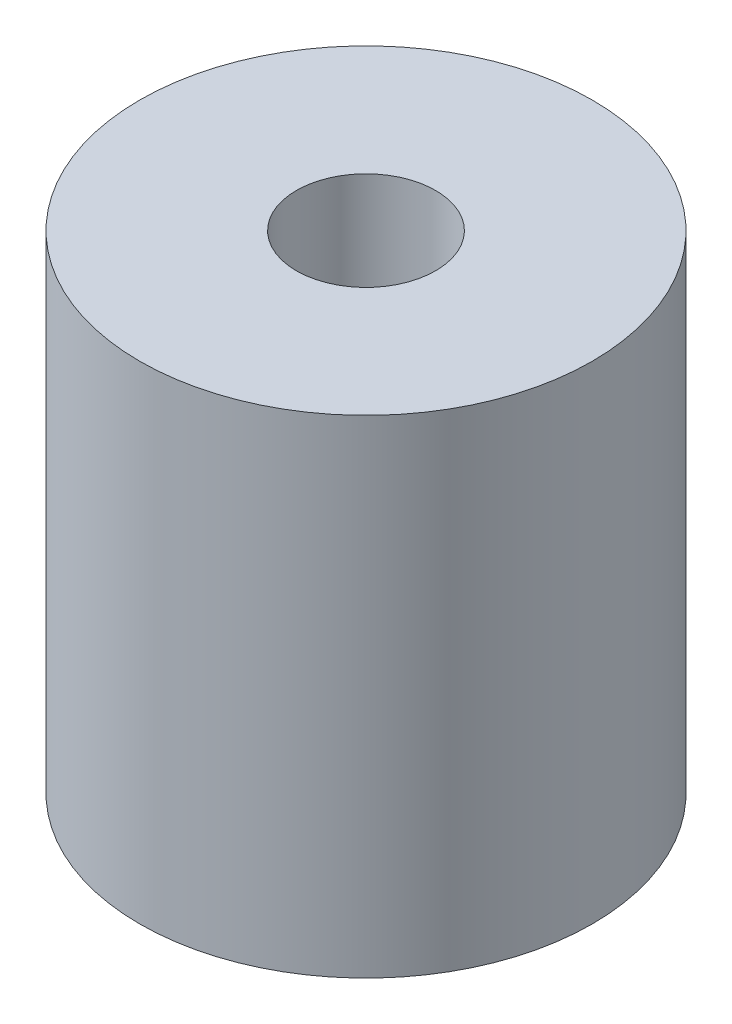
SolidWorks part; units mm, degrees
ref_plane "Alzado" through (0, 0, 0) normal (0, 0, 1) x (1, 0, 0)
ref_plane "Planta" through (0, 0, 0) normal (0, 1, 0) x (1, 0, 0)
ref_plane "Vista lateral" through (0, 0, 0) normal (1, 0, 0) x (0, 0, -1)
sketch "Croquis1" plane through (0, 0, 0) normal (0, 1, 0) x (1, 0, 0)
  circle A0 centre (0, 0) radius 6.5
  dimension "D1" = 13
extrude "Saliente-Extruir1" add sketch "Croquis1" along normal blind 14
sketch "Croquis2" plane through (0, 14, 0) normal (0, 1, 0) x (1, 0, 0)
  circle A0 centre (0, 0) radius 2
  dimension "D1" = 4
extrude "Cortar-Extruir1" cut sketch "Croquis2" against normal up to next
